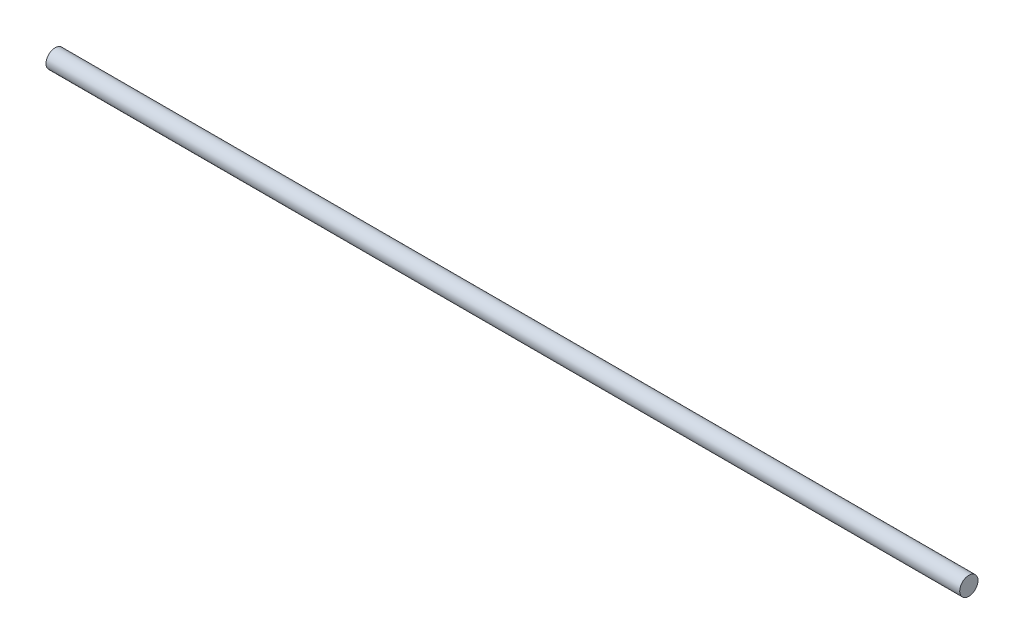
SolidWorks part; units mm, degrees
ref_plane "Alzado" through (0, 0, 0) normal (0, 0, 1) x (1, 0, 0)
ref_plane "Planta" through (0, 0, 0) normal (0, 1, 0) x (1, 0, 0)
ref_plane "Vista lateral" through (0, 0, 0) normal (1, 0, 0) x (0, 0, -1)
sketch "Croquis1" plane through (0, 0, 0) normal (1, 0, 0) x (0, 0, -1)
  circle A0 centre (0, 0) radius 4
  dimension "D1" = 8
extrude "Saliente-Extruir1" add sketch "Croquis1" along normal blind 400
sketch "Croquis4" plane through (0, 0, 0) normal (-1, 0, 0) x (0, 0, 1)
  circle A0 centre (0, 0) radius 4
  dimension "D1" = 8
